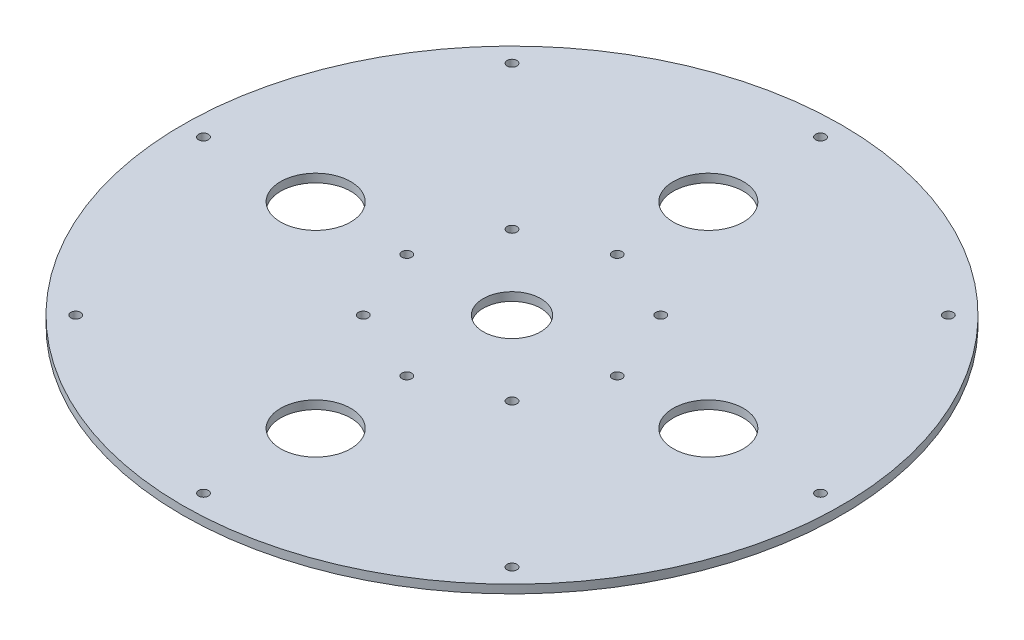
SolidWorks part; units mm, degrees
ref_plane "Front Plane" through (0, 0, 0) normal (0, 0, 1) x (1, 0, 0)
ref_plane "Top Plane" through (0, 0, 0) normal (0, 1, 0) x (1, 0, 0)
ref_plane "Right Plane" through (0, 0, 0) normal (1, 0, 0) x (0, 0, -1)
sketch "Sketch1" plane through (0, 0, 0) normal (0, 1, 0) x (1, 0, 0)
  line L0 (0, 129.9401) -> (0, -146.4852) construction
  line L1 (-129.3315, 0) -> (137.7007, 0) construction
  circle A0 centre (0, 0) radius 117.5
  circle A1 centre (0, 0) radius 10.25
  circle A12 centre (0, 0) radius 110 construction
  circle A13 centre (0, 70) radius 12.5
  circle A14 centre (70, 0) radius 12.5
  circle A15 centre (0, -70) radius 12.5
  circle A16 centre (-70, 0) radius 12.5
  circle A17 centre (0, 0) radius 70 construction
  circle A18 centre (0, 110) radius 1.75
  circle A19 centre (77.7817, 77.7817) radius 1.75
  circle A20 centre (110, 0) radius 1.75
  circle A21 centre (77.7817, -77.7817) radius 1.75
  circle A22 centre (0, -110) radius 1.75
  circle A23 centre (-77.7817, -77.7817) radius 1.75
  circle A24 centre (-110, 0) radius 1.75
  circle A25 centre (-77.7817, 77.7817) radius 1.75
  circle A26 centre (0, 37.5) radius 1.75
  circle A27 centre (26.5165, 26.5165) radius 1.75
  circle A28 centre (37.5, 0) radius 1.75
  circle A29 centre (26.5165, -26.5165) radius 1.75
  circle A30 centre (0, -37.5) radius 1.75
  circle A31 centre (-26.5165, -26.5165) radius 1.75
  circle A32 centre (-37.5, 0) radius 1.75
  circle A33 centre (-26.5165, 26.5165) radius 1.75
  circle A34 centre (0, 0) radius 37.5 construction
  point P29 (0, 0)
  point P42 (0, 0)
  point P57 (0, 0)
  dimension "D1" = 235
  dimension "D2" = 20.5
  dimension "D3" = 220
  dimension "D4" = 140
  dimension "D6" = 4
  dimension "D5" = 25
  dimension "D7" = 3.5
  dimension "D9" = 8
  dimension "D10" = 3.5
  dimension "D8" = 8
extrude "Boss-Extrude1" add sketch "Sketch1" along normal mid plane 3
